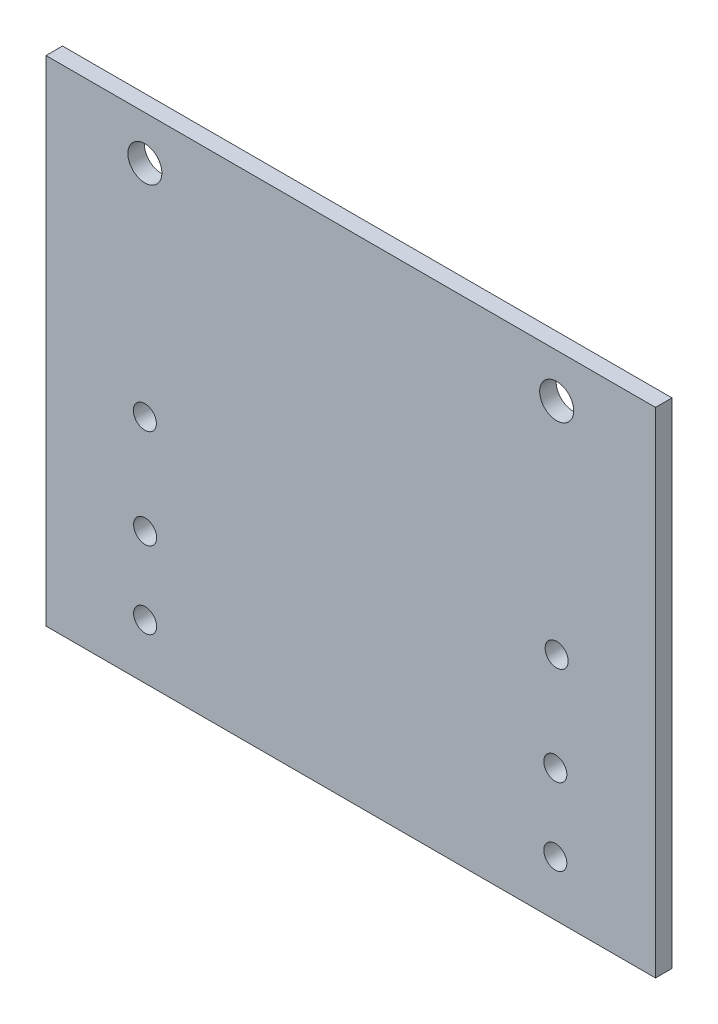
SolidWorks part; units mm, degrees
material "Stop 1060"
ref_plane "Płaszczyzna przednia" through (0, 0, 0) normal (0, 0, 1) x (1, 0, 0)
ref_plane "Płaszczyzna górna" through (0, 0, 0) normal (0, 1, 0) x (1, 0, 0)
ref_plane "Płaszczyzna prawa" through (0, 0, 0) normal (1, 0, 0) x (0, 0, -1)
sketch "Szkic1" plane through (0, 0, 0) normal (0, 0, 1) x (1, 0, 0)
  line L1 (0, 0) -> (111, 0)
  line L2 (0, 0) -> (0, 90)
  line L3 (0, 90) -> (111, 90)
  line L4 (111, 0) -> (111, 90)
  dimension "D1" = 111
  dimension "D2" = 90
extrude "Dodanie-wyciągnięcie1" add sketch "Szkic1" along normal blind 3
sketch "Szkic2" plane through (0, 0, 3) normal (0, 0, 1) x (1, 0, 0)
  line L4 (0, 90) -> (0, 0)
  line L5 (0, 0) -> (111, 0)
  line L6 (111, 0) -> (111, 90)
  line L7 (111, 90) -> (0, 90)
  line L8 (0, 90) -> (0, 0)
  line L9 (0, 0) -> (111, 0)
  line L10 (111, 0) -> (111, 90)
  line L11 (111, 90) -> (0, 90)
  circle A0 centre (18.05, 24) radius 2.1
  circle A1 centre (18.05, 10) radius 2.1
  circle A2 centre (92.75, 10) radius 2.1
  circle A3 centre (92.75, 24) radius 2.1
  dimension "D1" = 0
extrude "Wytnij-wyciągnięcie2" cut sketch "Szkic2" against normal through all contours A0 | A1 | A3 | A2
sketch "Szkic3" plane through (0, 0, 3) normal (0, 0, 1) x (1, 0, 0)
  line L0 (55.5, 90) -> (55.5, 33.1495) construction
  line L1 (111, 90) -> (0, 90) construction
  circle A0 centre (93, 82) radius 3.1
  circle A1 centre (93, 42) radius 2.1
  circle A2 centre (18, 42) radius 2.1
  circle A3 centre (18, 82) radius 3.1
extrude "Wytnij-wyciągnięcie3" cut sketch "Szkic3" against normal through all
